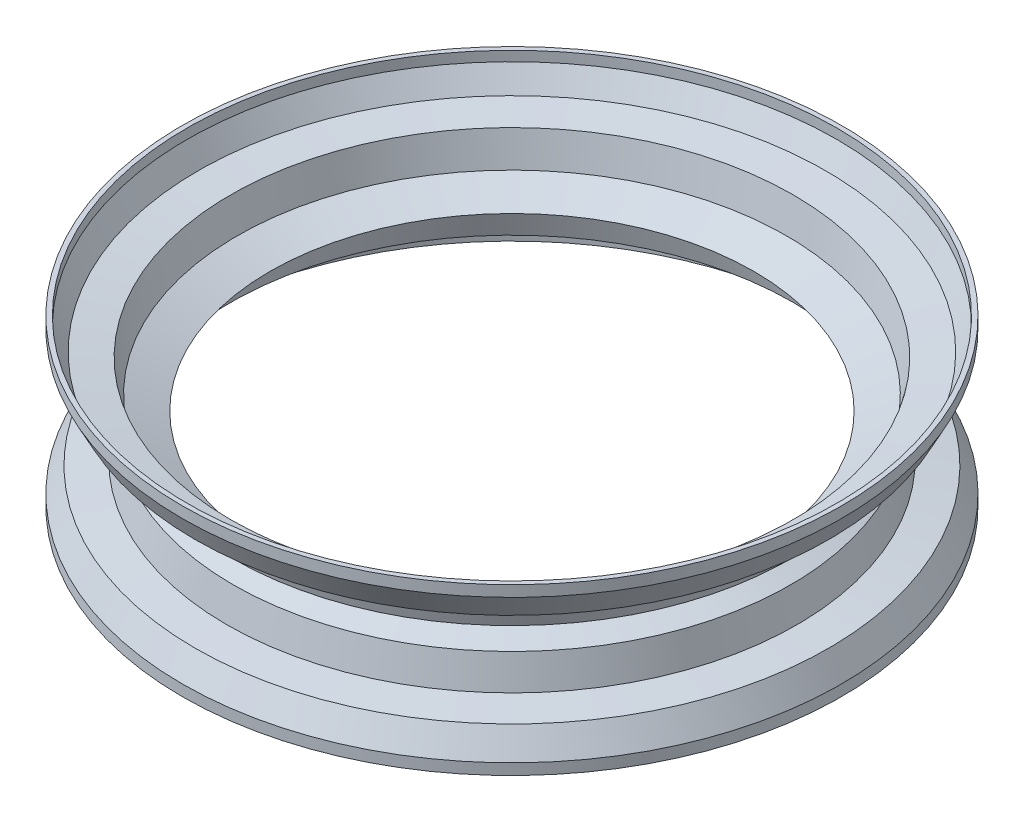
SolidWorks part; units mm, degrees
ref_plane "정면" through (0, 0, 0) normal (0, 0, 1) x (1, 0, 0)
ref_plane "윗면" through (0, 0, 0) normal (0, 1, 0) x (1, 0, 0)
ref_plane "우측면" through (0, 0, 0) normal (1, 0, 0) x (0, 0, -1)
sketch "스케치1" plane through (0, 0, 0) normal (0, 1, 0) x (1, 0, 0)
  circle A7 centre (0, 0) radius 35.8938
  point P2 (0, 0)
  point P3 (31.845, 16.5609)
  point P4 (26.927, 23.734)
  point P7 (13.793, 3.8888)
  point P14 (0, 0)
  dimension "D2" = 71.7876
extrude "보스-돌출1" add sketch "스케치1" along normal blind 1.2
ref_plane "평면1" through (0, 9, 0) normal (0, -1, 0) x (-1, 0, 0)
sketch "스케치3" plane through (0, 9, 0) normal (0, -1, 0) x (-1, 0, 0)
  circle A0 centre (0, 0) radius 27.5887
  dimension "D1" = 55.1775
sketch "스케치4" plane through (0, 0, 0) normal (1, 0, 0) x (0, 0, -1)
  line L0 (-29.665, 7.05) -> (-30.3496, 7.7789) construction
  line L1 (-27.5887, 9) -> (27.5887, 9) construction
  line L2 (0, 9) -> (0, 1.2) construction
  line L3 (35.8938, 1.2) -> (-35.8938, 1.2) construction
  line L4 (-35.8938, 1.2) -> (-34.5021, 3.8789)
  line L5 (-34.5021, 3.8789) -> (-31.0567, 4.3711)
  line L6 (-30.3496, 7.7789) -> (-31.0567, 4.3711)
  line L7 (-30.3496, 7.7789) -> (-27.5887, 9)
  line L8 (0, 9) -> (-27.5887, 9) construction
  line L9 (-31.7413, 5.1) -> (-31.0567, 4.3711) construction
  line L10 (-31.7413, 5.1) -> (-35.8938, 1.2) construction
  line L11 (-31.7413, 5.1) -> (-27.5887, 9) construction
  line L12 (-34.5021, 3.8789) -> (-33.8175, 3.15) construction
  line L13 (0, 9) -> (27.5887, 9) construction
  line L14 (-27.5887, 9) -> (0, 9)
  line L15 (0, 9) -> (0, 1.2)
  line L16 (-35.8938, 1.2) -> (0, 1.2)
  dimension "D1" = 55.1775
  dimension "D2" = 1
revolve "회전1" add sketch "스케치4" angle 360 about L15
mirror "대칭 복사1" about plane through (0, 9, 27.5887) normal (0, 1, 0) of "보스-돌출1", "회전1"
shell "쉘1" thickness 0.5
